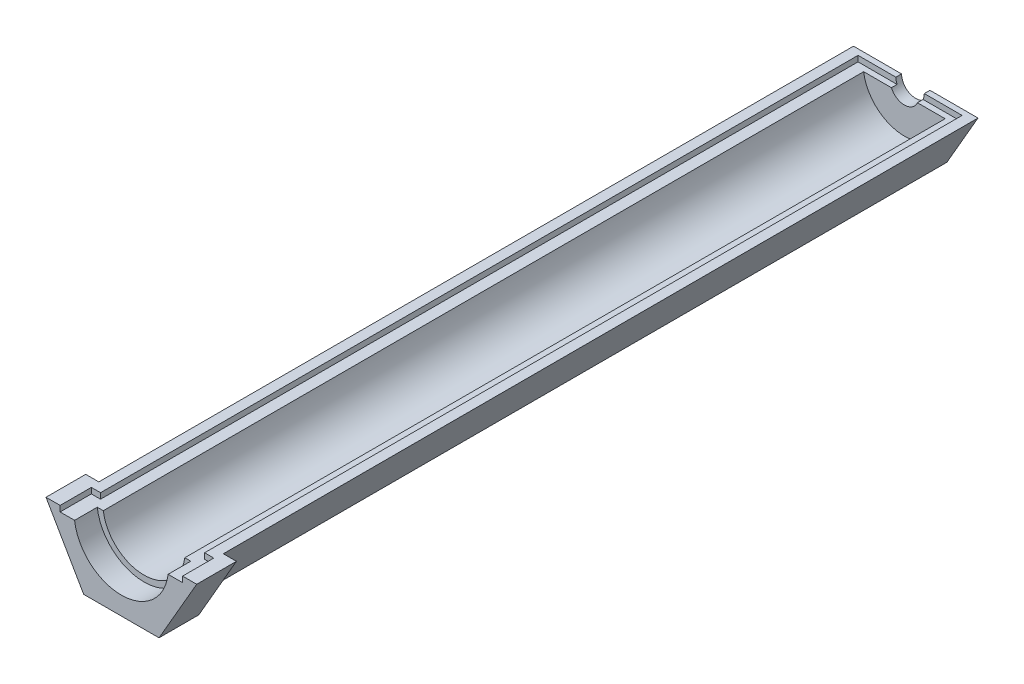
SolidWorks part; units mm, degrees
material "ABS"
ref_plane "Ebene vorne" through (0, 0, 0) normal (0, 0, 1) x (1, 0, 0)
ref_plane "Ebene oben" through (0, 0, 0) normal (0, 1, 0) x (1, 0, 0)
ref_plane "Ebene rechts" through (0, 0, 0) normal (1, 0, 0) x (0, 0, -1)
sketch "Skizze1" plane through (0, 0, 0) normal (0, 0, 1) x (1, 0, 0)
  line L0 (7.25, 0) -> (10.9697, 0)
  line L1 (-7.25, 0) -> (-10.9697, 0)
  line L3 (-10.9697, 0) -> (-5.4848, -9.5)
  line L4 (-5.4848, -9.5) -> (5.4848, -9.5)
  line L5 (5.4848, -9.5) -> (10.9697, 0)
  arc A0 (-7.25, 0) -> (7.25, 0) centre (0, 0) ccw
  dimension "D1" = 21.9393
  dimension "D2" = 60
  dimension "D4" = 9.5
extrude "Aufsatz-Linear austragen1" add sketch "Skizze1" along normal blind 136
sketch "Skizze2" plane through (0, 0, 0) normal (0, 0, 1) x (1, 0, 0)
  line L0 (7.25, 0) -> (-7.25, 0)
  arc A0 (-7.25, 0) -> (7.25, 0) centre (0, 0) ccw
  arc A1 (-7.25, 0) -> (7.25, 0) centre (0, 0) ccw construction
extrude "Aufsatz-Linear austragen2" add sketch "Skizze2" along normal blind 2
sketch3d "3D-Skizze5" plane through (0, 0, 0) normal (0, 0, 1) x (1, 0, 0)
  dimension "D1" = 133
sketch "Skizze3" plane through (0, 0, 133) normal (0, 0, 1) x (1, 0, 0)
  line L3 (-8.3, 0) -> (-13.2791, 0)
  line L4 (8.3, 0) -> (13.2791, 0)
  line L5 (-5.4848, -9.5) -> (5.4848, -9.5) construction
  line L6 (-7.25, 0) -> (-10.9697, 0) construction
  line L10 (-13.2791, 0) -> (-6.6395, -11.5)
  line L11 (-6.6395, -11.5) -> (6.6395, -11.5)
  line L12 (6.6395, -11.5) -> (13.2791, 0)
  line L16 (19.2833, -10.3997) -> (11.5579, 2.9811) [skipped]
  line L17 (15.576, 11.5) -> (0.1251, 11.5) [skipped]
  line L18 (-3.3785, 17.1483) -> (-11.1039, 3.7674) [skipped]
  arc A0 (8.3, 0) -> (-8.3, 0) centre (0, 0) cw
  dimension "D1" = 16.6
  dimension "D2" = 2
extrude "Aufsatz-Linear austragen3" add sketch "Skizze3" along normal blind 7
sketch "Skizze13" plane through (0, 0, 0) normal (0, 1, 0) x (1, 0, 0)
  line L0 (-10.7895, -140) -> (10.7895, -140)
  line L1 (13.2791, -140) -> (8.3, -140) construction
  line L2 (10.7895, -140) -> (10.7895, -134.5)
  line L3 (10.7895, -134.5) -> (9.1697, -134.5)
  line L4 (9.1697, -134.5) -> (9.1697, -1)
  line L5 (9.1697, -1) -> (-9.1697, -1)
  line L6 (-9.1697, -1) -> (-9.1697, -134.5)
  line L8 (-8.3, -140) -> (-13.2791, -140) construction
  line L9 (-10.7895, -140) -> (-10.7895, -134.5)
  line L10 (-10.7895, -134.5) -> (-9.1697, -134.5)
  line L18 (10.9697, -133) -> (10.9697, 0) construction
  line L19 (-10.9697, -133) -> (-10.9697, 0) construction
  line L20 (-5.7475, -133) -> (5.7475, -133) construction
  line L21 (13.2791, -133) -> (10.9697, -133) construction
  line L22 (10.9697, 0) -> (-10.9697, 0) construction
  dimension "D2" = 1.8
  dimension "D3" = 1.8
  dimension "D4" = 1.5
  dimension "D5" = 1.5
  dimension "D6" = 1
extrude "Schnitt-Linear austragen2" cut sketch "Skizze13" against normal blind 1
sketch "Skizze14" plane through (0, 0, 0) normal (0, 0, -1) x (-1, 0, 0)
  circle A0 centre (0, 0) radius 2.5
  dimension "D1" = 5
extrude "Schnitt-Linear austragen1" cut sketch "Skizze14" against normal up to surface (2 mm away) up to face at (0, -4.125, 2)
